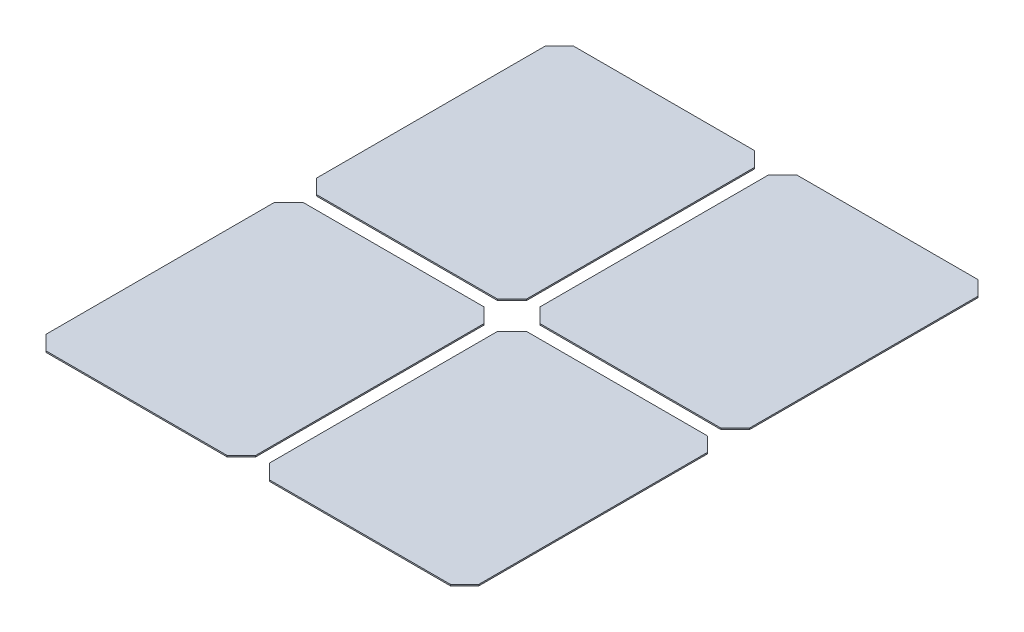
SolidWorks part; units mm, degrees
ref_plane "Front Plane" through (0, 0, 0) normal (0, 0, 1) x (1, 0, 0)
ref_plane "Top Plane" through (0, 0, 0) normal (0, 1, 0) x (1, 0, 0)
ref_plane "Right Plane" through (0, 0, 0) normal (1, 0, 0) x (0, 0, -1)
sketch "Sketch1" plane through (0, 0, 0) normal (0, 1, 0) x (1, 0, 0)
  line L0 (-168, 202.3934) -> (-157.3934, 213)
  line L1 (0, 0) -> (-346, 0) construction
  line L2 (0, 0) -> (0, 436) construction
  line L6 (-23.6066, 213) -> (-13, 202.3934)
  line L8 (-13, 33.6066) -> (-23.6066, 23)
  line L10 (-157.3934, 23) -> (-168, 33.6066)
  line L13 (-157.3934, 213) -> (-23.6066, 213)
  line L14 (-23.6066, 23) -> (-157.3934, 23)
  line L15 (-168, 33.6066) -> (-168, 202.3934)
  line L16 (-13, 202.3934) -> (-13, 33.6066)
  line L17 (0, 436) -> (-346, 436) construction
  line L18 (-346, 436) -> (-346, 0) construction
  line L19 (-333, 202.3934) -> (-322.3934, 213)
  line L20 (-188.6066, 213) -> (-178, 202.3934)
  line L21 (-178, 33.6066) -> (-188.6066, 23)
  line L22 (-322.3934, 23) -> (-333, 33.6066)
  line L23 (-322.3934, 213) -> (-188.6066, 213)
  line L24 (-188.6066, 23) -> (-322.3934, 23)
  line L25 (-333, 33.6066) -> (-333, 202.3934)
  line L26 (-178, 202.3934) -> (-178, 33.6066)
  line L27 (-333, 402.3934) -> (-322.3934, 413)
  line L28 (-188.6066, 413) -> (-178, 402.3934)
  line L29 (-178, 233.6066) -> (-188.6066, 223)
  line L30 (-322.3934, 223) -> (-333, 233.6066)
  line L31 (-322.3934, 413) -> (-188.6066, 413)
  line L32 (-188.6066, 223) -> (-322.3934, 223)
  line L33 (-333, 233.6066) -> (-333, 402.3934)
  line L34 (-178, 402.3934) -> (-178, 233.6066)
  line L35 (-168, 402.3934) -> (-157.3934, 413)
  line L36 (-23.6066, 413) -> (-13, 402.3934)
  line L37 (-13, 233.6066) -> (-23.6066, 223)
  line L38 (-157.3934, 223) -> (-168, 233.6066)
  line L39 (-157.3934, 413) -> (-23.6066, 413)
  line L40 (-23.6066, 223) -> (-157.3934, 223)
  line L41 (-168, 233.6066) -> (-168, 402.3934)
  line L42 (-13, 402.3934) -> (-13, 233.6066)
  dimension "D1" = 155
  dimension "D2" = 436
  dimension "D3" = 190
  dimension "D4" = 15
  dimension "D5" = 135
  dimension "D6" = 13
  dimension "D7" = 23
  dimension "D8" = 2
  dimension "D9" = 2
extrude "Boss-Extrude1" add sketch "Sketch1" along normal blind 1
